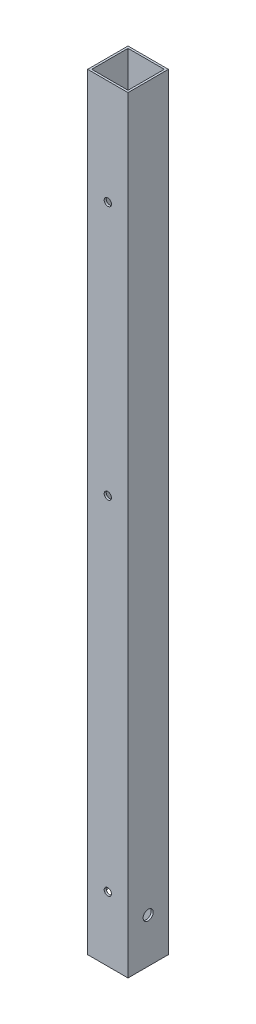
SolidWorks part; units mm, degrees
ref_plane "Front Plane" through (0, 0, 0) normal (0, 0, 1) x (1, 0, 0)
ref_plane "Top Plane" through (0, 0, 0) normal (0, 1, 0) x (1, 0, 0)
ref_plane "Right Plane" through (0, 0, 0) normal (1, 0, 0) x (0, 0, -1)
sketch "Sketch1" plane through (0, 0, 0) normal (0, 1, 0) x (1, 0, 0)
  line L0 (0, 0) -> (0, 25.4)
  line L1 (0, 25.4) -> (25.4, 25.4)
  line L2 (25.4, 25.4) -> (25.4, 0)
  line L3 (25.4, 0) -> (0, 0)
  line L6 (1.27, 12.3615) -> (1.27, 24.13)
  line L7 (1.27, 24.13) -> (12.7, 24.13)
  line L10 (12.7, 24.13) -> (24.13, 24.13)
  line L11 (24.13, 24.13) -> (24.13, 12.7)
  line L12 (24.13, 1.27) -> (24.13, 12.7)
  line L13 (24.13, 1.27) -> (12.7, 1.27)
  line L14 (1.27, 1.27) -> (12.7, 1.27)
  line L15 (1.27, 12.3615) -> (1.27, 1.27)
  dimension "D1" = 25.4
  dimension "D2" = 25.4
  dimension "D3" = 11.7685
  dimension "D4" = 11.0915
  dimension "D5" = 11.43
  dimension "D6" = 11.43
extrude "Boss-Extrude1" add sketch "Sketch1" along normal blind 482.6
sketch "Sketch2" plane through (0, 0, -25.4) normal (0, 0, -1) x (-1, 0, 0)
  line L0 (-25.4, 482.6) -> (0, 482.6) construction
  line L1 (-25.4, 482.6) -> (-25.4, 0) construction
  circle A0 centre (-12.7, 416.56) radius 2.286
  dimension "D3" = 4.572
  dimension "D1" = 66.04
  dimension "D2" = 12.7
extrude "Cut-Extrude1" cut sketch "Sketch2" against normal through all
sketch "Sketch3" plane through (0, 0, -25.4) normal (0, 0, -1) x (-1, 0, 0)
  line L1 (-25.4, 482.6) -> (-25.4, 0) construction
  line L2 (-25.4, 482.6) -> (0, 482.6) construction
  circle A0 centre (-12.7, 40.64) radius 2.286
  dimension "D3" = 4.572
  dimension "D1" = 441.96
  dimension "D2" = 12.7
extrude "Cut-Extrude2" cut sketch "Sketch3" against normal through all
sketch "Sketch4" plane through (0, 0, -25.4) normal (0, 0, -1) x (-1, 0, 0)
  line L0 (-25.4, 482.6) -> (0, 482.6) construction
  line L1 (-25.4, 482.6) -> (-25.4, 0) construction
  circle A0 centre (-12.7, 256.54) radius 2.286
  dimension "D2" = 4.572
  dimension "D1" = 226.06
  dimension "D3" = 12.7
extrude "Cut-Extrude3" cut sketch "Sketch4" against normal through all
sketch "Sketch9" plane through (0, 0, 0) normal (-1, 0, 0) x (0, 0, 1)
  line L0 (0, 482.6) -> (0, 0) construction
  line L1 (-25.4, 0) -> (0, 0) construction
  circle A0 centre (-12.7, 27.94) radius 3.175
  dimension "D3" = 6.35
  dimension "D1" = 12.7
  dimension "D2" = 27.94
extrude "Cut-Extrude8" cut sketch "Sketch9" against normal through all
